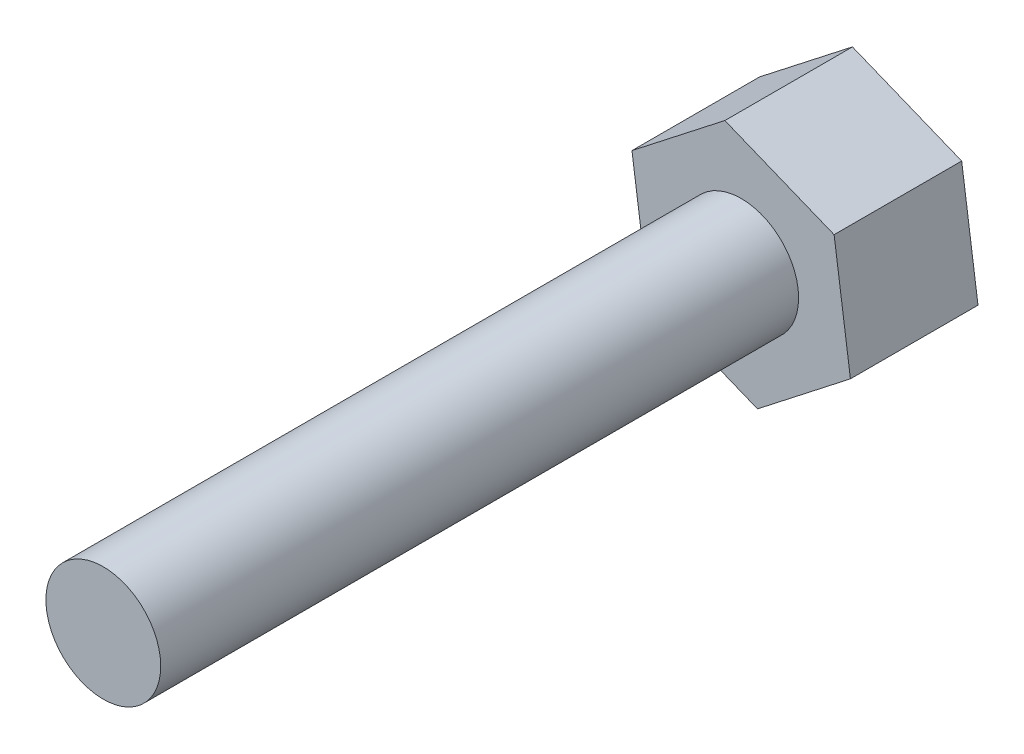
SolidWorks part; units mm, degrees
ref_plane "Front Plane" through (0, 0, 0) normal (0, 0, 1) x (1, 0, 0)
ref_plane "Top Plane" through (0, 0, 0) normal (0, 1, 0) x (1, 0, 0)
ref_plane "Right Plane" through (0, 0, 0) normal (1, 0, 0) x (0, 0, -1)
sketch "Sketch1" plane through (0, 0, 0) normal (0, 0, 1) x (1, 0, 0)
  line L1 (3.6419, 2.8407) -> (-0.6392, 4.5744)
  line L2 (-0.6392, 4.5744) -> (-4.2811, 1.7337)
  line L3 (-4.2811, 1.7337) -> (-3.6419, -2.8407)
  line L4 (-3.6419, -2.8407) -> (0.6392, -4.5744)
  line L5 (0.6392, -4.5744) -> (4.2811, -1.7337)
  line L6 (4.2811, -1.7337) -> (3.6419, 2.8407)
  circle A0 centre (0, 0) radius 4 construction
  dimension "D1" = 8
extrude "Boss-Extrude2" add sketch "Sketch1" along normal blind 5
sketch "Sketch2" plane through (0, 0, 5) normal (0, 0, 1) x (1, 0, 0)
  circle A0 centre (0, 0) radius 2.25
  dimension "D1" = 4.5
extrude "Boss-Extrude3" add sketch "Sketch2" along normal blind 25
